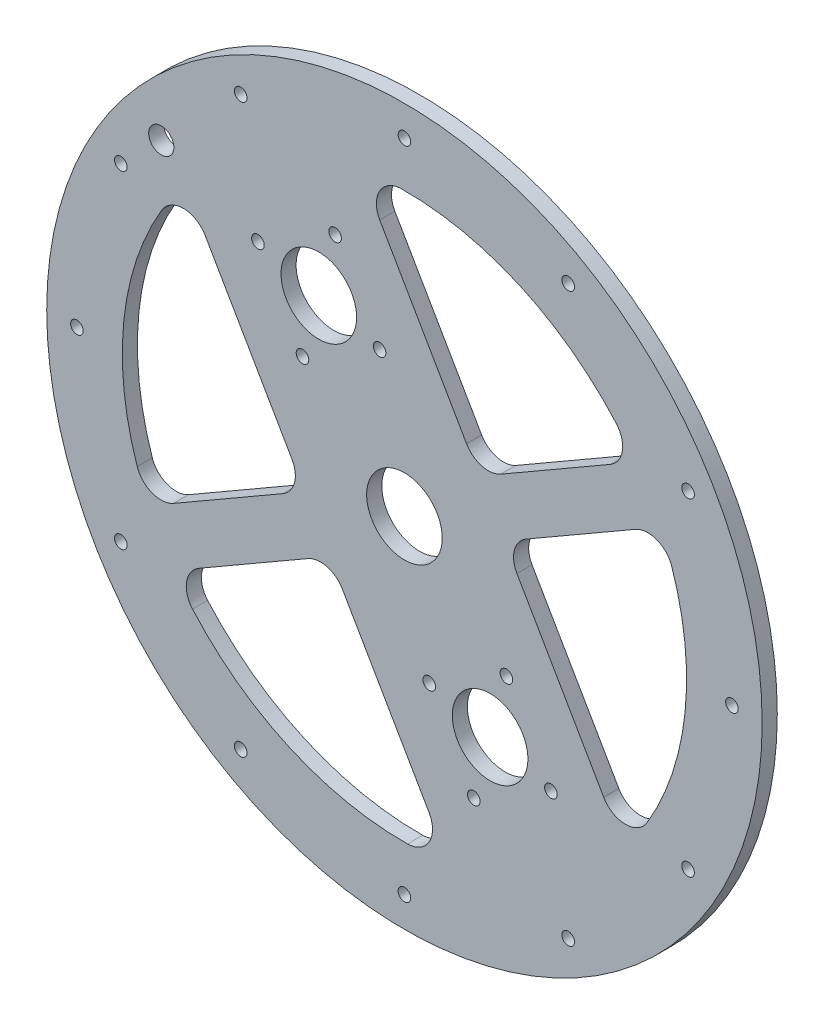
SolidWorks part; units mm, degrees
ref_plane "前视基准面" through (0, 0, 0) normal (0, 0, 1) x (1, 0, 0)
ref_plane "上视基准面" through (0, 0, 0) normal (0, 1, 0) x (1, 0, 0)
ref_plane "右视基准面" through (0, 0, 0) normal (1, 0, 0) x (0, 0, -1)
sketch "草图1" plane through (0, 0, 0) normal (0, 0, 1) x (1, 0, 0)
  line L0 (-28.1458, 48.75) -> (28.1458, -48.75) construction
  line L1 (0, 65) -> (-56.2917, 32.5) construction
  line L2 (-56.2917, 32.5) -> (-56.2917, -32.5) construction
  line L3 (-56.2917, -32.5) -> (0, -65) construction
  line L4 (0, -65) -> (56.2917, -32.5) construction
  line L5 (56.2917, -32.5) -> (56.2917, 32.5) construction
  line L6 (56.2917, 32.5) -> (0, 65) construction
  line L7 (-20.2352, 17.3708) -> (-4.9259, 26.2096) construction
  line L8 (-20.2352, 17.3708) -> (-29.0741, 32.6801) construction
  line L9 (-4.9259, 26.2096) -> (-13.7648, 41.5189) construction
  line L10 (-29.0741, 32.6801) -> (-13.7648, 41.5189) construction
  line L11 (-20.2352, 17.3708) -> (-13.7648, 41.5189) construction
  line L12 (-4.9259, 26.2096) -> (-29.0741, 32.6801) construction
  line L13 (0, 0) -> (56.2917, 32.5) construction
  line L14 (-65, 0) -> (0, 0) construction
  line L15 (-56.2917, 32.5) -> (0, 0) construction
  circle A0 centre (0, 0) radius 71
  circle A3 centre (0, 0) radius 56.2917 construction
  circle A4 centre (0, 65) radius 1.25
  circle A5 centre (56.2917, 32.5) radius 1.25
  circle A6 centre (56.2917, -32.5) radius 1.25
  circle A7 centre (0, -65) radius 1.25
  circle A8 centre (-56.2917, -32.5) radius 1.25
  circle A9 centre (-56.2917, 32.5) radius 1.25
  circle A10 centre (-29.0741, 32.6801) radius 1.25
  circle A11 centre (-13.7648, 41.5189) radius 1.25
  circle A12 centre (-4.9259, 26.2096) radius 1.25
  circle A13 centre (-20.2352, 17.3708) radius 1.25
  circle A14 centre (29.0741, -32.6801) radius 1.25
  circle A15 centre (20.2352, -17.3708) radius 1.25
  circle A16 centre (4.9259, -26.2096) radius 1.25
  circle A17 centre (13.7648, -41.5189) radius 1.25
  circle A18 centre (-17, 29.4449) radius 7.5
  circle A19 centre (17, -29.4449) radius 7.5
  circle A20 centre (32.5, 56.2917) radius 1.25
  circle A21 centre (-32.5, 56.2917) radius 1.25
  circle A22 centre (-65, 0) radius 1.25
  circle A23 centre (-32.5, -56.2917) radius 1.25
  circle A24 centre (32.5, -56.2917) radius 1.25
  circle A25 centre (65, 0) radius 1.25
  point P13 (-17, 29.4449)
  point P24 (0, 0)
  point P44 (0, 0)
  point P45 (0, 0)
  point P58 (0, 0)
  point P59 (-28.6895, 33.8726)
  dimension "D1" = 142
  dimension "D2" = 2.5
  dimension "D3" = 130
  dimension "D4" = 6
  dimension "D7" = 2.5
  dimension "D8" = 15
  dimension "D5" = 25
  dimension "D6" = 34
  dimension "D10" = 30
  dimension "D9" = 2
extrude "凸台-拉伸1" add sketch "草图1" along normal blind 3
cosmetic thread "装饰螺纹线1" parameters "D2"=3
cosmetic thread "装饰螺纹线2" parameters "D2"=3
cosmetic thread "装饰螺纹线3" parameters "D2"=3
cosmetic thread "装饰螺纹线4" parameters "D2"=3
cosmetic thread "装饰螺纹线5" parameters "D2"=3
cosmetic thread "装饰螺纹线6" parameters "D2"=3
cosmetic thread "装饰螺纹线7" parameters "D2"=3
cosmetic thread "装饰螺纹线8" parameters "D2"=3
cosmetic thread "装饰螺纹线9" parameters "D2"=3
cosmetic thread "装饰螺纹线10" parameters "D2"=3
cosmetic thread "装饰螺纹线11" parameters "D2"=3
cosmetic thread "装饰螺纹线12" parameters "D2"=3
cosmetic thread "装饰螺纹线13" parameters "D2"=3
cosmetic thread "装饰螺纹线14" parameters "D2"=3
cosmetic thread "装饰螺纹线15" parameters "D2"=3
cosmetic thread "装饰螺纹线16" parameters "D2"=3
cosmetic thread "装饰螺纹线17" parameters "D2"=3
cosmetic thread "装饰螺纹线18" parameters "D2"=3
cosmetic thread "装饰螺纹线19" parameters "D2"=3
cosmetic thread "装饰螺纹线20" parameters "D2"=3
sketch "草图2" plane through (0, 0, 3) normal (0, 0, 1) x (1, 0, 0)
  line L0 (0, 0) -> (0, 65) construction
  line L1 (0, 0) -> (-48.2608, 40.4956) construction
  circle A0 centre (0, 0) radius 63 construction
  circle A1 centre (-48.2608, 40.4956) radius 2.5
  dimension "D1" = 126
  dimension "D3" = 5
  dimension "D2" = 50
extrude "切除-拉伸1" cut sketch "草图2" against normal up to next
sketch "草图3" plane through (0, 0, 3) normal (0, 0, 1) x (1, 0, 0)
  line L0 (-17, 29.4449) -> (17, -29.4449) construction
  line L1 (-43.4739, 35.299) -> (-19.8205, -5.6699)
  line L2 (-8.8329, 55.299) -> (14.8205, 14.3301)
  line L3 (48.4974, 28) -> (-48.4974, -28) construction
  line L4 (14.8205, 14.3301) -> (45.8037, 32.2183)
  line L5 (-19.8205, -5.6699) -> (-50.8037, -23.558)
  line L6 (19.8205, 5.6699) -> (50.8037, 23.558)
  line L7 (-14.8205, -14.3301) -> (-45.8037, -32.2183)
  line L8 (19.8205, 5.6699) -> (43.4739, -35.299)
  line L9 (14.8205, 14.3301) -> (17.3205, 10) construction
  line L10 (17.3205, 10) -> (19.8205, 5.6699) construction
  line L11 (-14.8205, -14.3301) -> (8.8329, -55.299)
  line L12 (-17.3205, -10) -> (-14.8205, -14.3301) construction
  line L13 (-19.8205, -5.6699) -> (-17.3205, -10) construction
  arc A0 (-43.4739, 35.299) -> (-50.8037, -23.558) centre (0, 0) ccw
  circle A1 centre (0, 0) radius 71 construction
  arc A2 (-8.8329, 55.299) -> (-43.4739, 35.299) centre (0, 0) ccw construction
  arc A3 (43.4739, -35.299) -> (50.8037, 23.558) centre (0, 0) ccw
  arc A4 (8.8329, -55.299) -> (43.4739, -35.299) centre (0, 0) ccw construction
  arc A5 (45.8037, 32.2183) -> (-8.8329, 55.299) centre (0, 0) ccw
  arc A6 (50.8037, 23.558) -> (48.4974, 28) centre (0, 0) ccw construction
  arc A7 (48.4974, 28) -> (45.8037, 32.2183) centre (0, 0) ccw construction
  arc A8 (-45.8037, -32.2183) -> (8.8329, -55.299) centre (0, 0) ccw
  arc A9 (-50.8037, -23.558) -> (-48.4974, -28) centre (0, 0) ccw construction
  arc A10 (-48.4974, -28) -> (-45.8037, -32.2183) centre (0, 0) ccw construction
  dimension "D1" = 15
  dimension "D2" = 20
  dimension "D3" = 10
extrude "切除-拉伸2" cut sketch "草图3" against normal up to next
sketch "草图4" plane through (0, 0, 3) normal (0, 0, 1) x (1, 0, 0)
  circle A0 centre (0, 0) radius 7.5
  dimension "D1" = 15
extrude "切除-拉伸3" cut sketch "草图4" against normal up to next
fillet "圆角1" radius 5 12 edges at (-19.8205, -5.6699, 1.5) (-50.8037, -23.558, 1.5) (19.8205, 5.6699, 1.5) (50.8037, 23.558, 1.5) (43.4739, -35.299, 1.5) (14.8205, 14.3301, 1.5) (-8.8329, 55.299, 1.5) (45.8037, 32.2183, 1.5) (-14.8205, -14.3301, 1.5) (8.8329, -55.299, 1.5) (-45.8037, -32.2183, 1.5) (-43.4739, 35.299, 1.5)
